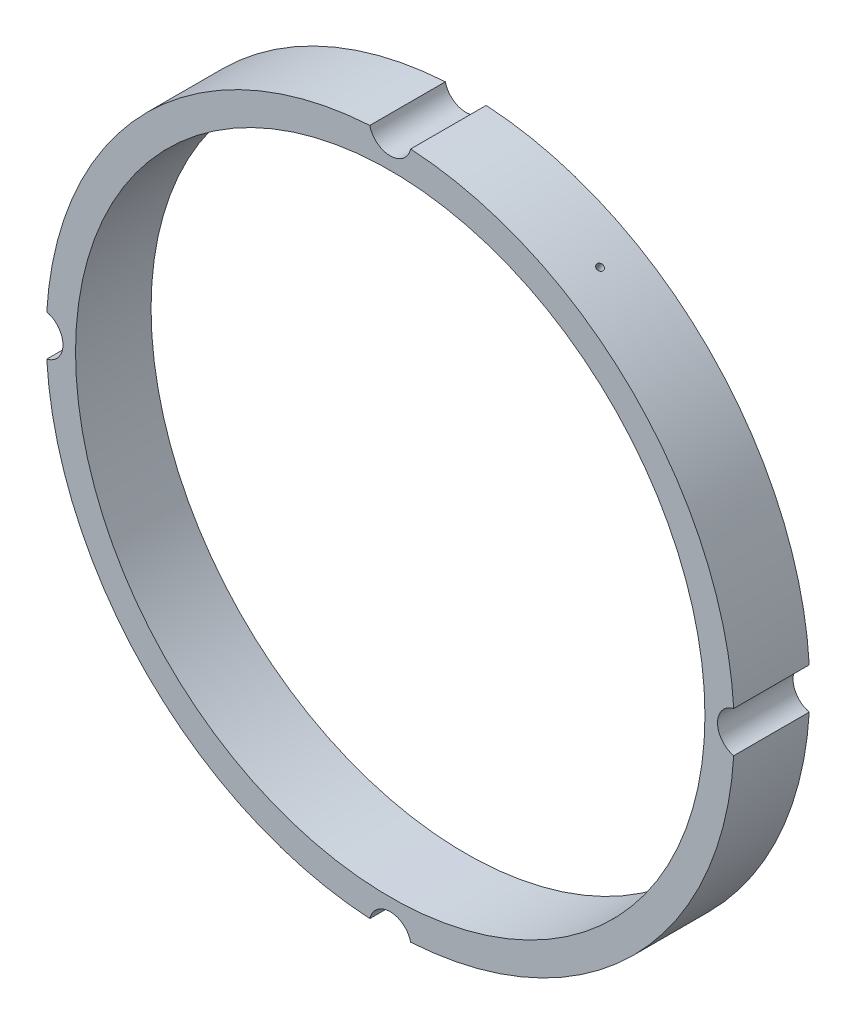
SolidWorks part; units mm, degrees
ref_plane "Front Plane" through (0, 0, 0) normal (0, 0, 1) x (1, 0, 0)
ref_plane "Top Plane" through (0, 0, 0) normal (0, 1, 0) x (1, 0, 0)
ref_plane "Right Plane" through (0, 0, 0) normal (1, 0, 0) x (0, 0, -1)
sketch "Sketch1" plane through (0, 0, 0) normal (0, 0, 1) x (1, 0, 0)
  circle A0 centre (0, 0) radius 75
  circle A1 centre (0, 0) radius 82
extrude "Boss-Extrude1" add sketch "Sketch1" along normal blind 18
sketch "Sketch2" plane through (0, 0, 18) normal (0, 0, 1) x (1, 0, 0)
  circle A0 centre (0, 83) radius 5
extrude "Cut-Extrude1" cut sketch "Sketch2" against normal through all
pattern_circular "CirPattern1" count 4 every 90 about axis through (0, 0, 0) along (0, 0, 1) of "Cut-Extrude1"
hole_wizard "M2x0.4 Tapped Hole1" positions "3DSketch1" profile "Sketch3" tap size "M2x0.4" standard "ANSI Metric"
sketch3d "3DSketch1"
  point P0 (41, 71.0141, 9)
sketch "Sketch3" plane through (41, 71.0141, 9) normal (0, 0, 1) x (-0.866, 0.5, 0)
  line L0 (0, 0) -> (0, 10.4807)
  line L1 (0, 10.4807) -> (0.8, 10)
  line L2 (0.8, 10) -> (0.8, 0)
  line L5 (0.8, 0) -> (0, 0)
  line L10 (0, 10.4807) -> (-0.8, 10) construction
  line L11 (0, -6.35) -> (0, 107.95) construction
  dimension "Tap Drill Dia." = 1.6
  dimension "Tap Drill Depth" = 10
  dimension "Drill Angle" = 118
cosmetic thread "Hole Thread1" parameters "D1"=4, "D2"=2
